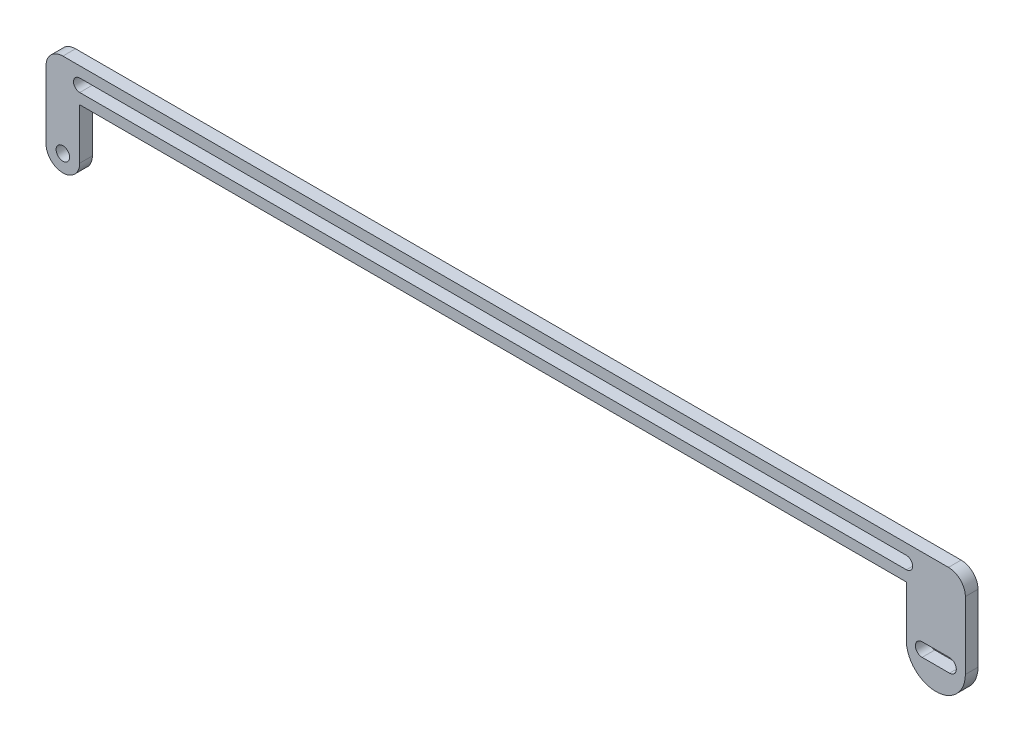
SolidWorks part; units mm, degrees
ref_plane "前视基准面" through (0, 0, 0) normal (0, 0, 1) x (1, 0, 0)
ref_plane "上视基准面" through (0, 0, 0) normal (0, 1, 0) x (1, 0, 0)
ref_plane "右视基准面" through (0, 0, 0) normal (1, 0, 0) x (0, 0, -1)
sketch "草图1" plane through (0, 0, 0) normal (0, 0, 1) x (1, 0, 0)
  line L0 (-53.8502, 4) -> (156.1498, 4)
  line L1 (-49.8502, -4) -> (146.1736, -4)
  line L2 (-49.8502, 0) -> (146.1736, 0) construction
  line L3 (-49.8502, 1.4835) -> (146.1736, 1.4835)
  line L4 (-49.8502, -1.4835) -> (146.1736, -1.4835)
  line L6 (152.1498, -1.6) -> (152.4837, -1.6)
  line L7 (-47.7619, 1.4835) -> (-10.1946, 1.4835)
  line L8 (160.1498, 0) -> (160.1498, -16)
  line L9 (149.9003, -14.4) -> (156.405, -14.4)
  line L10 (146.1736, -15.4961) -> (146.1736, -4)
  line L11 (-57.8502, 0) -> (-57.8502, -16)
  line L12 (-49.8502, -4) -> (-49.8502, -16)
  line L13 (146.1736, -4) -> (146.1736, -15.4961) construction
  line L14 (149.9003, -17.6) -> (156.405, -17.6)
  line L15 (153.1526, -17.6) -> (153.1526, -19.5072) construction
  arc A4 (-53.8502, 4) -> (-57.8502, 0) centre (-53.8502, 0) ccw
  arc A9 (-49.8502, 1.4835) -> (-49.8502, -1.4835) centre (-49.8502, 0) ccw
  arc A10 (146.1736, -1.4835) -> (146.1736, 1.4835) centre (146.1736, 0) ccw
  arc A12 (160.1498, 0) -> (156.1498, 4) centre (156.1498, 0) ccw construction
  arc A14 (156.1498, 4) -> (160.1498, 0) centre (156.1498, 0) cw
  arc A18 (160.1498, -16) -> (146.1736, -15.4961) centre (153.1526, -16) cw
  arc A19 (-53.8502, 4) -> (-57.8502, 0) centre (-53.8502, 0) ccw construction
  arc A20 (-57.8502, -16) -> (-49.8502, -16) centre (-53.8502, -16) ccw
  circle A21 centre (-53.8502, -16) radius 1.6
  arc A23 (156.405, -14.4) -> (156.405, -17.6) centre (156.405, -16) cw
  arc A24 (149.9003, -14.4) -> (149.9003, -17.6) centre (149.9003, -16) ccw
  point P5 (146.1736, 0)
  point P15 (48.1617, 0)
  point P22 (0, 0)
  point P31 (153.1526, -17.6)
  dimension "D1" = 210
  dimension "D3" = 16
  dimension "D4" = 16
  dimension "D7" = 8
extrude "凸台-拉伸1" add sketch "草图1" along normal blind 3
